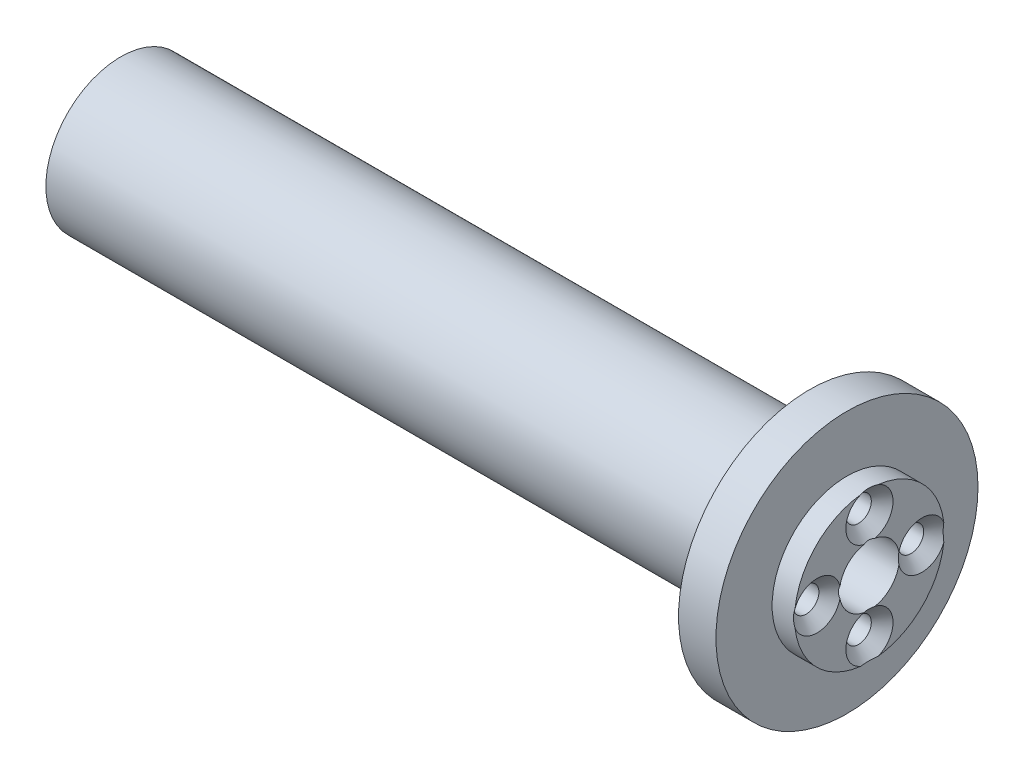
SolidWorks part; units mm, degrees
ref_plane "Front Plane" through (0, 0, 0) normal (0, 0, 1) x (1, 0, 0)
ref_plane "Top Plane" through (0, 0, 0) normal (0, 1, 0) x (1, 0, 0)
ref_plane "Right Plane" through (0, 0, 0) normal (1, 0, 0) x (0, 0, -1)
sketch "Sketch1" plane through (0, 0, 0) normal (0, 1, 0) x (1, 0, 0)
  line L1 (-3, 17.5) -> (-8, 17.5)
  line L2 (-8, 17.5) -> (-8, 10)
  line L3 (-8, 10) -> (-100, 10)
  line L4 (-100, 10) -> (-100, 0)
  line L5 (-100, 0) -> (0, 0) construction
  line L6 (0, 0) -> (-100, 0)
  line L7 (-3, 17.5) -> (-3, 10)
  line L8 (-3, 10) -> (0, 10)
  line L9 (0, 10) -> (0, 4)
  line L10 (0, 4) -> (-19, 4)
  line L11 (-19, 4) -> (-19, 0)
  dimension "D1" = 5
  dimension "D2" = 17.5
  dimension "D3" = 10
  dimension "D4" = 100
  dimension "D5" = 3
  dimension "D6" = 4
  dimension "D7" = 19
revolve "Revolve2" add sketch "Sketch1" angle 360 about L6
ref_plane "Plane1" through (-8, 0, 0) normal (-1, 0, 0) x (0, 0, 1)
split "Split1" trim tools "Plane1" bodies to split 102 resulting bodies 103 104
hole_wizard "CSK for M3 Countersunk Raised Head Screw2" positions "Sketch6" profile "Sketch7" countersink size "M3" standard "ISO"
sketch "Sketch6" plane through (0, 0, 0) normal (1, 0, 0) x (0, 0, -1)
  line L2 (0, -10) -> (0, -4) construction
  line L3 (0, -4) -> (0, 4) construction
  circle A9 centre (0, 0) radius 7 construction
  circle A10 centre (0, 0) radius 10 construction
  circle A11 centre (0, 0) radius 10 construction
  circle A12 centre (0, 0) radius 4 construction
  point P77 (0, 7)
  point P79 (7, 0)
  point P82 (0, -7)
  point P83 (-7, 0)
sketch "Sketch7" plane through (0, 0, 7) normal (0, 1, 0) x (0, 0, -1)
  line L0 (0, 0) -> (0, 11.0215)
  line L1 (0, 11.0215) -> (1.7, 10)
  line L2 (1.7, 10) -> (1.7, 1.45)
  line L3 (1.7, 1.45) -> (3.15, 0)
  line L5 (3.15, 0) -> (0, 0)
  line L6 (-1.7, 1.45) -> (-3.15, 0) construction
  line L10 (0, 11.0215) -> (-1.7, 10) construction
  line L11 (0, -6.35) -> (0, 107.95) construction
  dimension "Hole Dia." = 3.4
  dimension "Hole Depth" = 10
  dimension "Near C'Sink Dia." = 6.3
  dimension "Near C'Sink Angle" = 90
  dimension "Drill Angle" = 118
ref_plane "Plane2" through (0, 0, -10) normal (0, 0, -1) x (-1, 0, 0)
hole_wizard "M4 Tapped Hole2" positions "Sketch12" profile "Sketch11" tap size "M4" standard "ISO"
sketch "Sketch12" plane through (0, 0, -10) normal (0, 0, -1) x (-1, 0, 0)
  line L0 (19.25, 0) -> (-19.25, 0) construction
  line L1 (8, 10) -> (8, -10) construction
  point P1 (16, 0)
  dimension "D1" = 8
sketch "Sketch11" plane through (-16, 0, 0) normal (1, 0, 0) x (0, -0.7071, -0.7071)
  line L0 (0, 0) -> (0, 206206.942)
  line L1 (0, 206206.942) -> (1.65, 206205.9506)
  line L2 (1.65, 206205.9506) -> (1.65, 0)
  line L5 (1.65, 0) -> (0, 0)
  line L10 (0, 206206.942) -> (-1.65, 206205.9506) construction
  line L11 (0, -6.35) -> (0, 107.95) construction
  dimension "Tap Drill Dia." = 3.3
  dimension "Tap Drill Depth" = 206205.9506
  dimension "Drill Angle" = 118
cosmetic thread "Hole Thread2"
